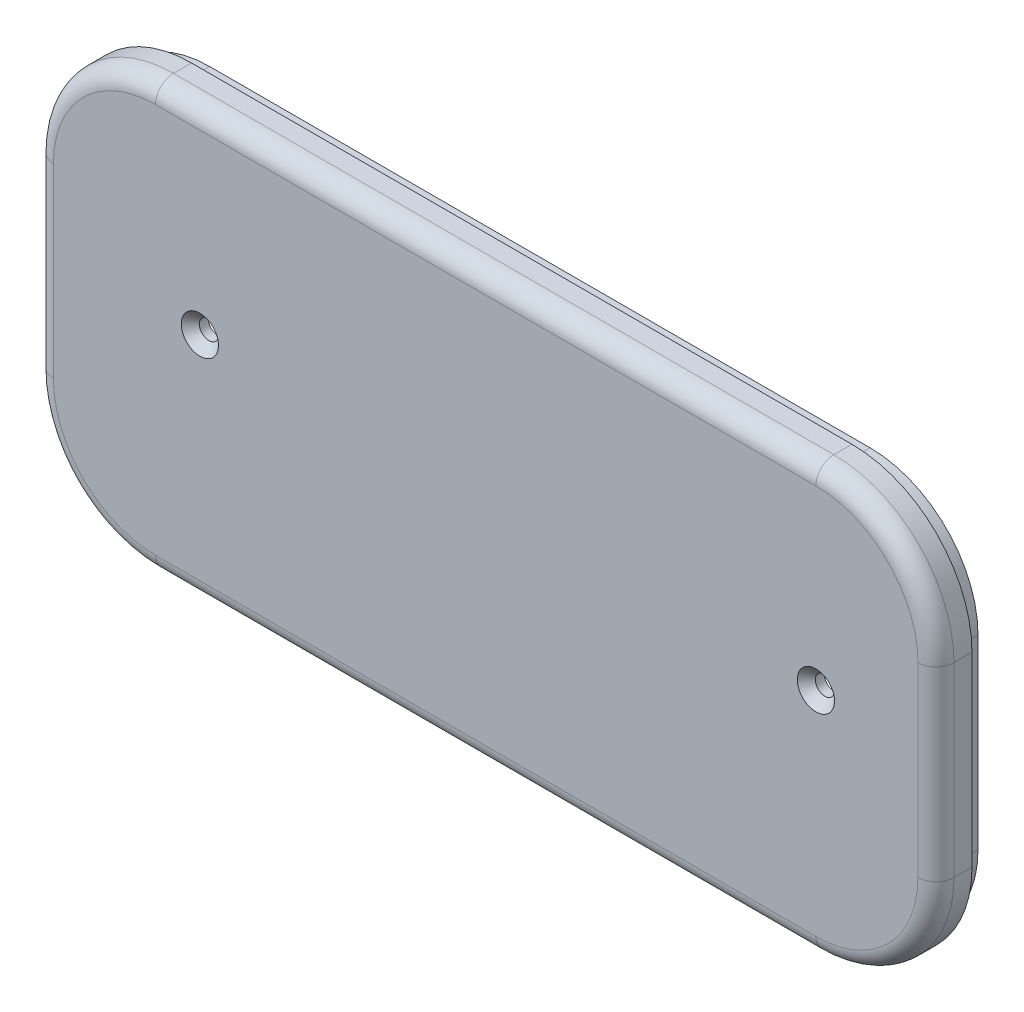
SolidWorks part; units mm, degrees
ref_plane "Front Plane" through (0, 0, 0) normal (0, 0, 1) x (1, 0, 0)
ref_plane "Top Plane" through (0, 0, 0) normal (0, 1, 0) x (1, 0, 0)
ref_plane "Right Plane" through (0, 0, 0) normal (1, 0, 0) x (0, 0, -1)
sketch "Sketch1" plane through (0, 0, 0) normal (0, 0, 1) x (1, 0, 0)
  line L8 (67.5, -46) -> (67.5, -15)
  line L9 (47.5, 5) -> (-62.5, 5)
  line L10 (-82.5, -15) -> (-82.5, -46)
  line L11 (-62.5, -66) -> (47.5, -66)
  arc A8 (47.5, -66) -> (67.5, -46) centre (47.5, -46) ccw
  arc A9 (67.5, -15) -> (47.5, 5) centre (47.5, -15) ccw
  arc A10 (-62.5, 5) -> (-82.5, -15) centre (-62.5, -15) ccw
  arc A11 (-82.5, -46) -> (-62.5, -66) centre (-62.5, -46) ccw
extrude "Boss-Extrude1" add sketch "Sketch1" along normal blind 3
sketch "Sketch2" plane through (0, 0, 0) normal (0, 0, -1) x (-1, 0, 0)
  line L0 (-47.5, -64) -> (62.5, -64)
  line L1 (80.5, -46) -> (80.5, -15)
  line L2 (62.5, 3) -> (-47.5, 3)
  line L3 (-65.5, -15) -> (-65.5, -46)
  line L4 (-47.5, -66) -> (62.5, -66)
  line L5 (82.5, -46) -> (82.5, -15)
  line L6 (62.5, 5) -> (-47.5, 5)
  line L7 (-67.5, -15) -> (-67.5, -46)
  line L8 (-47.5, -66) -> (62.5, -66)
  line L9 (82.5, -46) -> (82.5, -15)
  line L10 (62.5, 5) -> (-47.5, 5)
  line L11 (-67.5, -15) -> (-67.5, -46)
  arc A0 (62.5, -64) -> (80.5, -46) centre (62.5, -46) ccw
  arc A1 (80.5, -15) -> (62.5, 3) centre (62.5, -15) ccw
  arc A2 (-47.5, 3) -> (-65.5, -15) centre (-47.5, -15) ccw
  arc A3 (-65.5, -46) -> (-47.5, -64) centre (-47.5, -46) ccw
  arc A4 (-67.5, -46) -> (-47.5, -66) centre (-47.5, -46) ccw
  arc A5 (62.5, -66) -> (82.5, -46) centre (62.5, -46) ccw
  arc A6 (82.5, -15) -> (62.5, 5) centre (62.5, -15) ccw
  arc A7 (-47.5, 5) -> (-67.5, -15) centre (-47.5, -15) ccw
  arc A8 (-67.5, -46) -> (-47.5, -66) centre (-47.5, -46) ccw
  arc A9 (62.5, -66) -> (82.5, -46) centre (62.5, -46) ccw
  arc A10 (82.5, -15) -> (62.5, 5) centre (62.5, -15) ccw
  arc A11 (-47.5, 5) -> (-67.5, -15) centre (-47.5, -15) ccw
  dimension "D1" = 0
  dimension "D2" = 2
extrude "Boss-Extrude2" add sketch "Sketch2" along normal blind 3
fillet "Fillet1" radius 3 8 edges at (-7.5, -66, 3) (-76.6421, -60.1421, 3) (-82.5, -30.5, 3) (-76.6421, -0.8579, 3) (-7.5, 5, 3) (61.6421, -0.8579, 3) (67.5, -30.5, 3) (61.6421, -60.1421, 3)
sketch "Sketch3" plane through (0, 0, 0) normal (0, 0, -1) x (-1, 0, 0)
  line L0 (-62.5, -15) -> (-62.5, -46)
  line L1 (-47.5, -61) -> (62.5, -61)
  line L2 (77.5, -46) -> (77.5, -15)
  line L3 (62.5, 0) -> (-47.5, 0)
  line L4 (-65.5, -15) -> (-65.5, -46)
  line L5 (-47.5, -64) -> (62.5, -64)
  line L6 (80.5, -46) -> (80.5, -15)
  line L7 (62.5, 3) -> (-47.5, 3)
  line L8 (-65.5, -15) -> (-65.5, -46)
  line L9 (-47.5, -64) -> (62.5, -64)
  line L10 (80.5, -46) -> (80.5, -15)
  line L11 (62.5, 3) -> (-47.5, 3)
  arc A0 (-62.5, -46) -> (-47.5, -61) centre (-47.5, -46) ccw
  arc A1 (62.5, -61) -> (77.5, -46) centre (62.5, -46) ccw
  arc A2 (77.5, -15) -> (62.5, 0) centre (62.5, -15) ccw
  arc A3 (-47.5, 0) -> (-62.5, -15) centre (-47.5, -15) ccw
  arc A4 (-65.5, -46) -> (-47.5, -64) centre (-47.5, -46) ccw
  arc A5 (62.5, -64) -> (80.5, -46) centre (62.5, -46) ccw
  arc A6 (80.5, -15) -> (62.5, 3) centre (62.5, -15) ccw
  arc A7 (-47.5, 3) -> (-65.5, -15) centre (-47.5, -15) ccw
  arc A8 (-65.5, -46) -> (-47.5, -64) centre (-47.5, -46) ccw
  arc A9 (62.5, -64) -> (80.5, -46) centre (62.5, -46) ccw
  arc A10 (80.5, -15) -> (62.5, 3) centre (62.5, -15) ccw
  arc A11 (-47.5, 3) -> (-65.5, -15) centre (-47.5, -15) ccw
  dimension "D1" = 0
  dimension "D2" = 3
extrude "Boss-Extrude3" add sketch "Sketch3" along normal blind 6
sketch "Sketch4" plane through (0, 0, 0) normal (0, 0, -1) x (-1, 0, 0)
  circle A0 centre (-47.5, -27.5) radius 1.6
  circle A1 centre (55.1, -27.5) radius 1.6
extrude "Cut-Extrude1" cut sketch "Sketch4" against normal up to surface (3 mm away) up to face at (-7.5, -30.5, 3)
chamfer "Chamfer1" distance 1.5 angle 45 2 edges at (49.1, -27.5, 3) (-53.5, -27.5, 3)
sketch "Sketch5" plane through (0, 0, -6) normal (0, 0, -1) x (-1, 0, 0)
  line L0 (-44.4338, 0) -> (-55.3088, 0)
  line L1 (57.5, 0) -> (-52.5, 0) construction
  line L2 (-55.3088, 0) -> (-60.5001, -7.5168)
  line L3 (-44.4338, 0) -> (-60.5001, -7.5168)
  arc A0 (-47.5, 0) -> (-62.5, -15) centre (-47.5, -15) ccw construction
extrude "Cut-Extrude2" cut sketch "Sketch5" against normal up to surface (6 mm away) up to face at (45.9, -27.5, 0)
